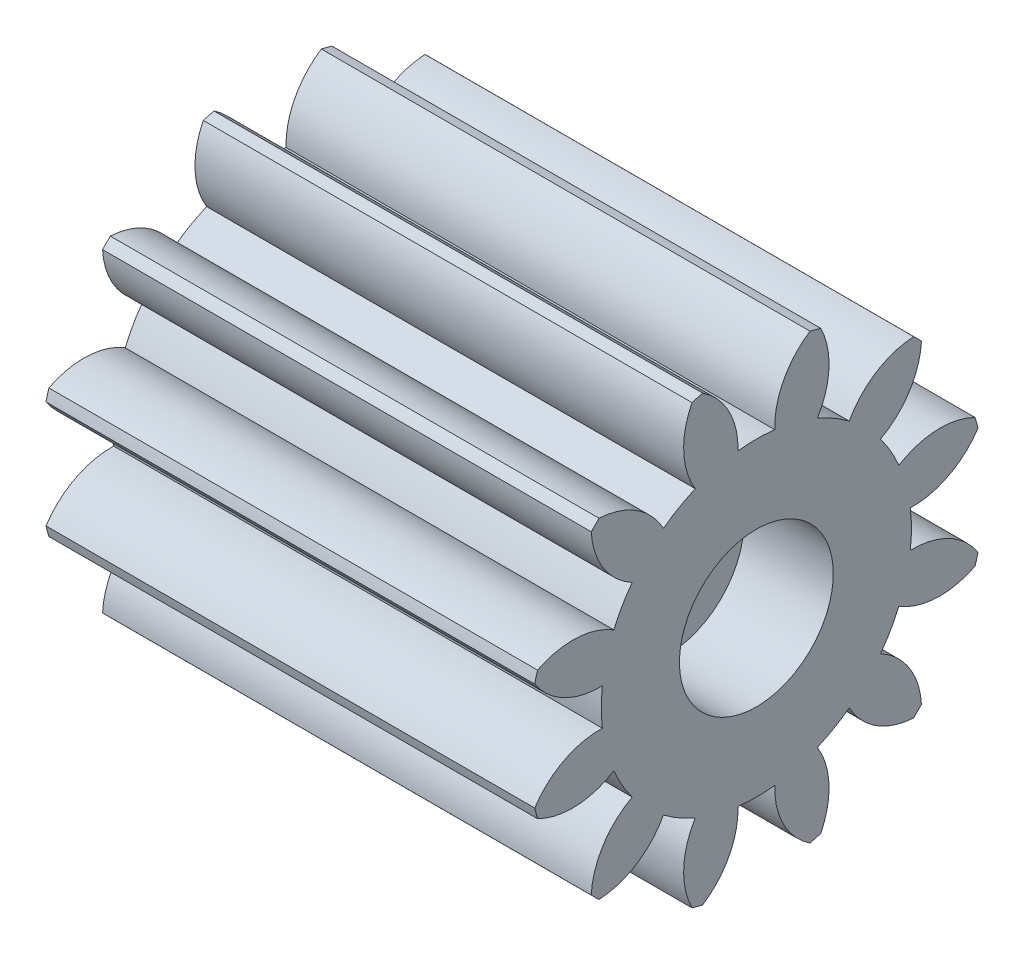
SolidWorks part; units mm, degrees
material "ABS"
ref_plane "Plane1" through (0, 0, 0) normal (0, 0, 1) x (1, 0, 0)
ref_plane "Plane2" through (0, 0, 0) normal (0, 1, 0) x (1, 0, 0)
ref_plane "Plane3" through (0, 0, 0) normal (1, 0, 0) x (0, 0, -1)
other "Configuration Table"
sketch "HoldingSke" plane through (0, 0, 0) normal (0, 1, 0) x (1, 0, 0)
  line L0 (0, 0) -> (496.899, -105.6191)
  line L1 (-15, 0) -> (100, 0) construction
  line L2 (0, 0) -> (-2.1039, 2.3779)
  line L3 (0, 0) -> (-11.863, 4.5341)
  line L4 (0, 0) -> (8.4473, 1.7955)
  line L5 (0, 0) -> (-47.5972, -17.7524)
  line L6 (0, 0) -> (-15.7917, -10.6547)
  line L7 (-2.1039, 2.3779) -> (8.8311, 51.9886)
  line L8 (-76.2, 54.61) -> (-72.771, 54.61)
  line L9 (-71.009, 38.7566) -> (-53.1078, 45.2721)
  line L10 (-76.2, 71.12) -> (104.1128, 71.12)
  line L11 (0, 0) -> (-19.05, 0)
  line L12 (-76.2, 101.6) -> (-76.1492, 101.6)
  line L13 (24.9733, 27.94) -> (52.9518, 28.4284)
  line L14 (24.9733, 27.94) -> (25.0241, 27.9398)
  line L15 (24.9733, 27.94) -> (100.4021, 29.52)
  circle A0 centre (0, 0) radius 1.5875
  circle A1 centre (0, 0) radius 6.0452
  circle A2 centre (0, 0) radius 38.1
  circle A3 centre (0, 0) radius 1.5875
  dimension "MHD" = 12.0904
  dimension "Hub_dia" = 76.2
  dimension "Bore" = 3.175
  dimension "MBD" = 3.175
  dimension "Num_teeth" = 12
  dimension "Pitch" = 508
  dimension "Overall_len" = 50.8
  dimension "Show_teeth" = 12
  dimension "Thickness" = 19.05
  dimension "OAL" = 50.8016
  dimension "T_dim" = 3.429
  dimension "Ap" = 20
  dimension "H" = 19.05
  dimension "Pitch_radius" = 180.3128
  dimension "Width" = 19.05
  dimension "Backlash" = 0.0508
  dimension "Addendum_fac" = 1
  dimension "Dedendum_fac" = 1.2
  dimension "Clearance_fac" = 0.2
  dimension "Dedendum_add" = 0.0508
sketch "BasProSke" plane through (0, 0, 0) normal (0, 1, 0) x (1, 0, 0)
  line L0 (-10, 0) -> (60, 0) construction
  line L1 (0, 0) -> (0, 8.89)
  line L2 (0, 0) -> (19.05, 0)
  line L3 (19.05, 0) -> (19.05, 8.89)
  line L4 (19.05, 8.89) -> (0, 8.89)
  dimension "Thickness" = 19.05
  dimension "Diameter" = 17.78
revolve "Base-Revolve" add sketch "BasProSke" angle 360 about L0
sketch "TooCutSke" plane through (0, 0, 0) normal (1, 0, 0) x (0, 0, -1)
  line L1 (0, 0) -> (0, 107) construction
  line L2 (0, 0) -> (-1.0834, 7.5426) construction
  line L3 (0, 0) -> (-3.9164, 14.6164) construction
  line L4 (-1.0834, 7.5426) -> (-1.9582, 7.3082) construction
  arc A0 (0.7171, 6.0025) -> (-0.7171, 6.0025) centre (0, 0) ccw
  arc A1 (2.1216, 8.6593) -> (-2.1216, 8.6593) centre (0, 0) ccw
  circle A2 centre (0, 0) radius 7.62 construction
  circle A3 centre (0, 0) radius 7.1605 construction
  arc A4 (-0.7171, 6.0025) -> (-2.1216, 8.6593) centre (-3.7638, 6.0915) ccw
  arc A5 (2.1216, 8.6593) -> (0.7171, 6.0025) centre (3.7638, 6.0915) ccw
  dimension "Root_dia" = 12.0904
  dimension "Overcut_dia" = 17.8308
  dimension "Pitch_dia" = 15.24
  dimension "Base_dia" = 14.3209
  dimension "Flank_rad" = 3.048
  dimension "Half_ang" = 15
  dimension "Half_CT" = 0.9057
extrude "ToothCut" cut sketch "TooCutSke" along normal through all
fillet "Breaks" [suppressed] radius 0.0254
fillet "RootFillets" [suppressed] radius 0.3048
pattern_circular "TeethCuts" count 12 every 30 about axis through (-10, 0, 0) along (1, 0, 0) of "ToothCut", "RootFillets", "Breaks"
sketch "HubNeaOneSke" plane through (0, 0, 0) normal (-1, 0, 0) x (0, 0, 1)
  circle A0 centre (0, 0) radius 6.0452
  dimension "Diameter" = 12.0904
extrude "HubNearOne" [suppressed] add sketch "HubNeaOneSke" along normal blind 31.7516
sketch "HubNeaBotSke" plane through (0, 0, 0) normal (-1, 0, 0) x (0, 0, 1)
  circle A0 centre (0, 0) radius 6.0452
  dimension "Diameter" = 12.0904
extrude "HubNearBoth" [suppressed] add sketch "HubNeaBotSke" along normal blind 15.8758
ref_plane "FarPln" through (19.05, 0, 0) normal (1, 0, 0) x (0, 0, -1)
sketch "HubFarSke" plane through (19.05, 0, 0) normal (1, 0, 0) x (0, 0, -1)
  circle A0 centre (0, 0) radius 6.0452
  dimension "Diameter" = 12.0904
extrude "HubFar" [suppressed] add sketch "HubFarSke" along normal blind 15.8758
sketch "BorSke" plane through (0, 0, 0) normal (1, 0, 0) x (0, 0, -1)
  circle A0 centre (0, 0) radius 1.5875
  dimension "Diameter" = 3.175
extrude "Bore" cut sketch "BorSke" along normal mid plane 101.6031
sketch "KeySke" plane through (0, 0, 0) normal (1, 0, 0) x (0, 0, -1)
  line L0 (-0.127, 0) -> (-0.127, 1.8415)
  line L1 (-0.127, 1.8415) -> (0.127, 1.8415)
  line L2 (0.127, 1.8415) -> (0.127, 0)
  line L3 (0, 0) -> (0, 34) construction
  line L4 (-0.127, 0) -> (0.127, 0)
  dimension "Offset" = 1.8415
  dimension "Width" = 0.254
extrude "Keyway" [suppressed] cut sketch "KeySke" along normal mid plane 101.6031
pattern_circular "Keyway2" [suppressed] count 2 every 90 about axis through (-10, 0, 0) along (1, 0, 0)
sketch "Sketch1" plane through (0, 0, 0) normal (-1, 0, 0) x (0, 0, 1)
  circle A0 centre (0, 0) radius 3
  dimension "D1" = 6
extrude "Cut-Extrude1" cut sketch "Sketch1" along normal blind 3.4798 from surface at -19.05 starting at face at (19.05, 0, 1.5875)
sketch "Sketch3" plane through (0, 0, 0) normal (-1, 0, 0) x (0, 0, 1)
  point P0 (0, 0)
hole_wizard "M3 Clearance Hole1" positions "3DSketch3" profile "Sketch4" hole size "M3" standard "ANSI Metric" end condition through all
sketch3d "3DSketch3"
  point P0 (0, 0, 0)
sketch "Sketch4" plane through (0, 0, 0) normal (0, 1, 0) x (0, 0, 1)
  line L0 (0, 0) -> (0, 19.05)
  line L1 (0, 19.05) -> (1.7, 19.05)
  line L2 (1.7, 19.05) -> (1.7, 0)
  line L5 (1.7, 0) -> (0, 0)
  line L11 (0, -6.35) -> (0, 107.95) construction
  dimension "Thru Hole Dia." = 3.4
  dimension "Thru Hole Depth" = 19.05
equation "' \"Pitch@HoldingSke\" = 4"
equation "' \"Num_teeth@HoldingSke\" = 12"
equation "' \"Ap@HoldingSke\" =  20"
equation "' \"Ap@HoldingSke\" = 20"
equation "'\"Width@HoldingSke\" = 0.5"
equation "' \"Hub_dia@HoldingSke\"= 1"
equation "' \"Hub_dia@HoldingSke\" = 1"
equation "' \"Overall_len@HoldingSke\" = 1.0"
equation "' \"Bore@HoldingSke\" = 0.75"
equation "' \"T_dim@HoldingSke\" = 0.85"
equation "' \"Width@KeySke\" = 0.25"
equation "' \"Show_teeth@HoldingSke\" = 13"
equation "' \"Backlash@HoldingSke\" = 0.009"
equation "' \"Addendum_fac@HoldingSke\" = 1.0"
equation "' \"Dedendum_fac@HoldingSke\" = 1.25"
equation "' \"Dedendum_add@HoldingSke\" = 0.00005"
equation "' \"Clearance_fac@HoldingSke\" = 0.25"
equation "' \"Pitch@HoldingSke\" = 0.5"
equation "' \"Num_teeth@HoldingSke\" = 23"
equation "' \"Show_teeth@HoldingSke\" = 23"
equation "' \"Backlash@HoldingSke\" = 0.0375"
equation "\"Overcut_dia@TooCutSke\" = (\"Num_teeth@HoldingSke\" + 2 * \"Addendum_fac@HoldingSke\") / \"Pitch@HoldingSke\" + 0.002"
equation "\"Pitch_dia@TooCutSke\" = \"Num_teeth@HoldingSke\" / \"Pitch@HoldingSke\""
equation "\"Base_dia@TooCutSke\" = \"Num_teeth@HoldingSke\" / \"Pitch@HoldingSke\" * cos((\"Ap@HoldingSke\"  * 3.14159265 / 180))"
equation "\"Root_dia@TooCutSke\" = (\"Num_teeth@HoldingSke\" + 2) / \"Pitch@HoldingSke\" - 2 * (\"Addendum_fac@HoldingSke\" + \"Dedendum_fac@HoldingSke\") / \"Pitch@HoldingSke\" - \"Dedendum_add@HoldingSke\" * 2"
equation "\"Half_ang@TooCutSke\" = 180 / \"Num_teeth@HoldingSke\""
equation "\"Half_CT@TooCutSke\" = \"Num_teeth@HoldingSke\" / \"Pitch@HoldingSke\" * sin((3.14159265 / 2 / \"Num_teeth@HoldingSke\")) / 2 - 7 * \"Backlash@HoldingSke\" / 4"
equation "\"Flank_rad@TooCutSke\" = \"Num_teeth@HoldingSke\" / \"Pitch@HoldingSke\" / 5"
equation "\"Radius@RootFillets\" = \"Clearance_fac@HoldingSke\" / \"Pitch@HoldingSke\" + \"Dedendum_add@HoldingSke\""
equation "\"Break_rad@Breaks\" = 0.02 / \"Pitch@HoldingSke\""
equation "\"Thickness@HoldingSke\" = \"Width@HoldingSke\""
equation "\"OAL@HoldingSke\" = \"Thickness@HoldingSke\""
equation "\"MHD@HoldingSke\" = (\"Num_teeth@HoldingSke\" + 2) / \"Pitch@HoldingSke\" - 2 * (\"Addendum_fac@HoldingSke\" + \"Dedendum_fac@HoldingSke\")  / \"Pitch@HoldingSke\" - \"Dedendum_add@HoldingSke\" * 2"
equation "\"MBD@HoldingSke\" = (\"Num_teeth@HoldingSke\" + 2) / \"Pitch@HoldingSke\" - 2 * (\"Addendum_fac@HoldingSke\" + \"Dedendum_fac@HoldingSke\")  / \"Pitch@HoldingSke\" - \"Dedendum_add@HoldingSke\" * 2 - 0.002"
equation "\"MHD@HoldingSke\" = ((sgn( \"MHD@HoldingSke\" - \"Hub_dia@HoldingSke\" )-1)*( \"MHD@HoldingSke\" - \"Hub_dia@HoldingSke\" ))/-2+ \"Hub_dia@HoldingSke\""
equation "\"MBD@HoldingSke\" = ((sgn( \"MBD@HoldingSke\" - \"Bore@HoldingSke\" )-1)*( \"MBD@HoldingSke\" - \"Bore@HoldingSke\" ))/-2+ \"Bore@HoldingSke\""
equation "\"OAL@HoldingSke\" = ((sgn( \"OAL@HoldingSke\" - \"Overall_len@HoldingSke\" )+1)*( \"OAL@HoldingSke\" - \"Overall_len@HoldingSke\" ))/2 + \"Overall_len@HoldingSke\" + 0.000002"
equation "\"Num_teeth@TeethCuts\" = int( \"Show_teeth@HoldingSke\" ) + 1"
equation "\"Num_teeth@TeethCuts\" = ((sgn( \"Num_teeth@TeethCuts\" - \"Num_teeth@HoldingSke\" )-1)*( \"Num_teeth@TeethCuts\" - \"Num_teeth@HoldingSke\" ))/-2+ \"Num_teeth@HoldingSke\""
equation "\"Num_teeth@TeethCuts\" = ((sgn( \"Num_teeth@TeethCuts\" - 2.0)+1)*( \"Num_teeth@TeethCuts\" - 2.0))/2 +2.0"
equation "\"Angle@TeethCuts\" = 360.0 / \"Num_teeth@HoldingSke\""
equation "\"Diameter@BasProSke\" = (\"Num_teeth@HoldingSke\" + 2 * \"Addendum_fac@HoldingSke\") / \"Pitch@HoldingSke\""
equation "\"Thickness@BasProSke\"  = \"Thickness@HoldingSke\""
equation "' \"Fillet_rad@BasProSke\" =  \"Thickness@HoldingSke\" * 0.05"
equation "' \"Fillet_rad@BasProSke\" = \"Thickness@HoldingSke\" * 0.05"
equation "\"MHD@HoldingSke\" = ((sgn( \"MHD@HoldingSke\" - \"Root_dia@TooCutSke\" )-1)*( \"MHD@HoldingSke\" - \"Root_dia@TooCutSke\" ))/-2+ \"Root_dia@TooCutSke\""
equation "\"Diameter@HubNeaOneSke\" = \"MHD@HoldingSke\""
equation "\"Length@HubNearOne\" = \"OAL@HoldingSke\" - \"Thickness@BasProSke\""
equation "\"Diameter@HubNeaBotSke\" = \"MHD@HoldingSke\""
equation "\"Length@HubNearBoth\" = ( \"OAL@HoldingSke\" - \"Thickness@BasProSke\" ) / 2.0"
equation "\"Thickness@FarPln\" = \"Thickness@BasProSke\""
equation "\"Diameter@HubFarSke\" = \"MHD@HoldingSke\""
equation "\"Length@HubFar\" = ( \"OAL@HoldingSke\" - \"Thickness@BasProSke\" ) / 2.0"
equation "\"Diameter@BorSke\" = \"MBD@HoldingSke\""
equation "\"D1@Bore\" = \"OAL@HoldingSke\" * 2.0"
equation "\"D1@Keyway\" = \"OAL@HoldingSke\" * 2.0"
equation "\"Offset@KeySke\" = \"T_dim@HoldingSke\" - \"MBD@HoldingSke\" / 2.0"
